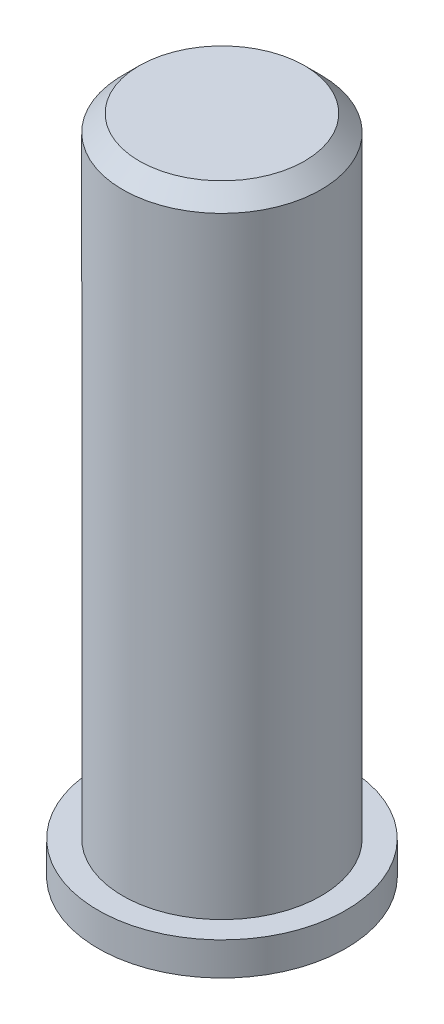
SolidWorks part; units mm, degrees
ref_plane "Спереди" through (0, 0, 0) normal (0, 0, 1) x (1, 0, 0)
ref_plane "Сверху" through (0, 0, 0) normal (0, 1, 0) x (1, 0, 0)
ref_plane "Справа" through (0, 0, 0) normal (1, 0, 0) x (0, 0, -1)
sketch "Эскиз1" plane through (0, 0, 0) normal (0, 1, 0) x (1, 0, 0)
  circle A0 centre (0, 0) radius 3
  dimension "D1" = 6
extrude "Вытянуть1" add sketch "Эскиз1" along normal blind 20
chamfer "Фаска1" distance 0.5 angle 45 1 edges at (0, 20, 3)
sketch "Эскиз2" plane through (0, 0, 0) normal (0, -1, 0) x (1, 0, 0)
  circle A0 centre (0, 0) radius 3.75
  dimension "D1" = 7.5
extrude "Вытянуть2" add sketch "Эскиз2" against normal blind 1
sketch "Эскиз3" plane through (0, 0, 0) normal (0, -1, 0) x (1, 0, 0)
  circle A0 centre (0, 0) radius 0.375
  dimension "D1" = 0.75
extrude "Вытянуть3" add sketch "Эскиз3" along normal blind 0.8
